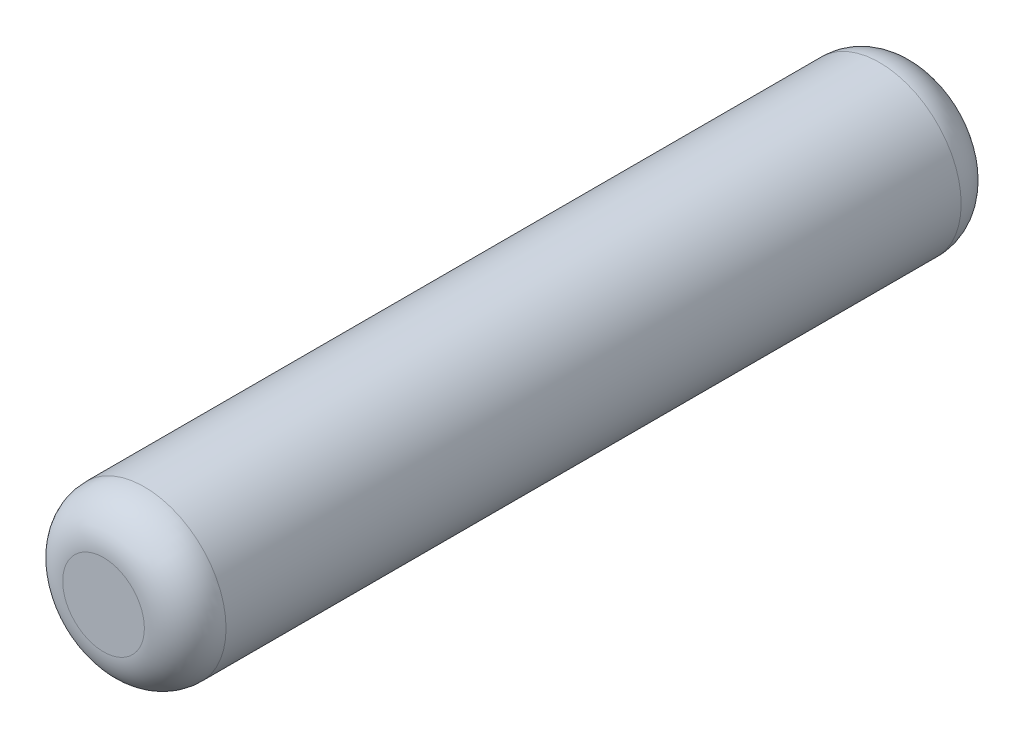
SolidWorks part; units mm, degrees
ref_plane "前视基准面" through (0, 0, 0) normal (0, 0, 1) x (1, 0, 0)
ref_plane "上视基准面" through (0, 0, 0) normal (0, 1, 0) x (1, 0, 0)
ref_plane "右视基准面" through (0, 0, 0) normal (1, 0, 0) x (0, 0, -1)
sketch "草图1" plane through (0, 0, 0) normal (0, 0, 1) x (1, 0, 0)
  circle A0 centre (0, 0) radius 1
  dimension "D1" = 2
extrude "凸台-拉伸1" add sketch "草图1" along normal blind 10
fillet "圆角1" radius 0.5 2 edges at (1, 0, 0) (1, 0, 10)
